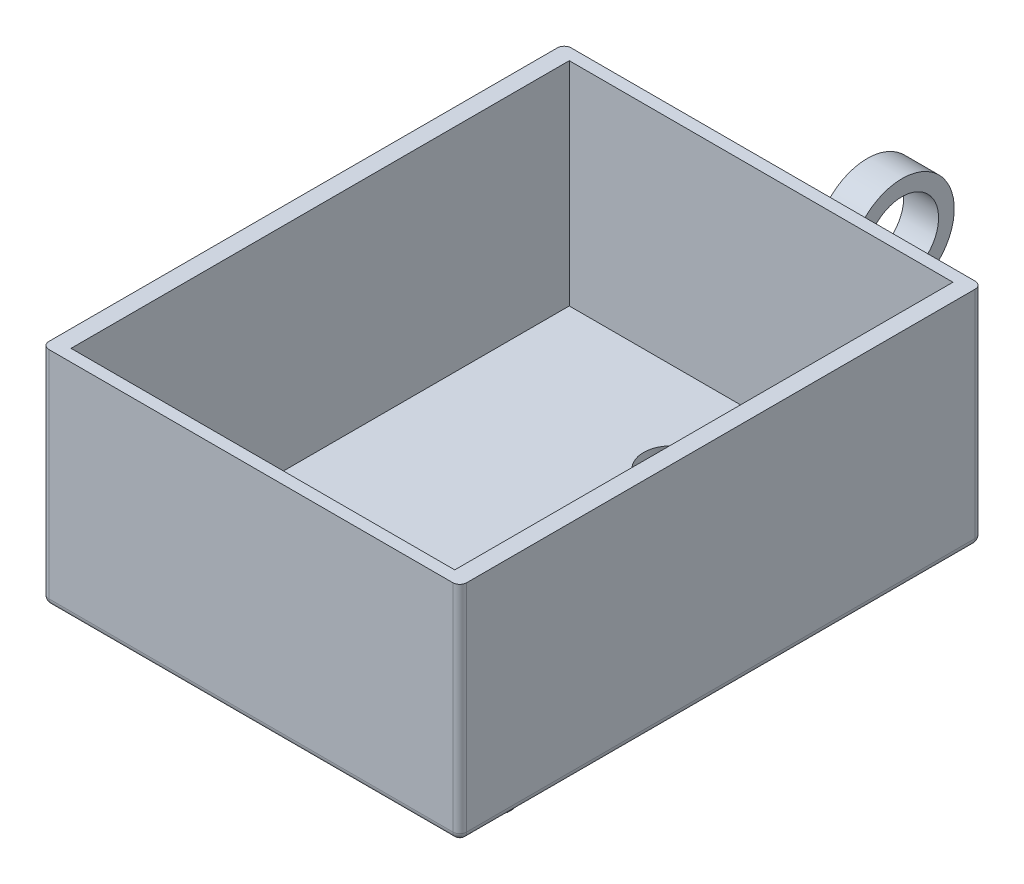
SolidWorks part; units mm, degrees
ref_plane "Front Plane" through (0, 0, 0) normal (0, 0, 1) x (1, 0, 0)
ref_plane "Top Plane" through (0, 0, 0) normal (0, 1, 0) x (1, 0, 0)
ref_plane "Right Plane" through (0, 0, 0) normal (1, 0, 0) x (0, 0, -1)
sketch "Sketch1" plane through (0, 0, 0) normal (0, 0, 1) x (1, 0, 0)
  line L1 (0, 0) -> (60, 0)
  line L2 (0, 0) -> (0, 32)
  line L3 (0, 32) -> (60, 32)
  line L4 (60, 0) -> (60, 32)
  dimension "D1" = 32
  dimension "D2" = 60
extrude "Boss-Extrude1" add sketch "Sketch1" along normal blind 75
sketch "Sketch2" plane through (0, 32, 0) normal (0, 1, 0) x (1, 0, 0)
  line L0 (0, 0) -> (2.452, -1.7285)
  line L1 (57.548, -1.7285) -> (60, 0)
  line L2 (2.452, -1.7285) -> (57.548, -1.7285)
  line L3 (2.452, -1.7285) -> (2.452, -73.2715)
  line L4 (2.452, -73.2715) -> (57.548, -73.2715)
  line L5 (57.548, -1.7285) -> (57.548, -73.2715)
  line L6 (0, -75) -> (2.452, -73.2715)
  line L7 (60, -75) -> (57.548, -73.2715)
  dimension "D1" = 3
extrude "Cut-Extrude1" cut sketch "Sketch2" along direction (0, -1, 0) on the side against the normal offset from surface (30.5 mm away) 1.5 contours L5 L2 L3 L4
sketch "Sketch3" plane through (0, 0, 0) normal (0, 0, -1) x (-1, 0, 0)
  line L0 (-30, 32) -> (-30, 0)
  line L1 (-60, 32) -> (0, 32) construction
  line L2 (0, 0) -> (-60, 0) construction
  line L4 (-32.5, 13.5) -> (-27.5, 13.5)
  line L5 (-32.5, 13.5) -> (-32.5, 18.5)
  line L6 (-32.5, 18.5) -> (-27.5, 18.5)
  line L7 (-27.5, 13.5) -> (-27.5, 18.5)
  line L8 (-32.5, 13.5) -> (-27.5, 18.5) construction
  line L9 (-32.5, 18.5) -> (-27.5, 13.5) construction
  point P6 (-30, 16)
  dimension "D1" = 5
  dimension "D2" = 5
extrude "Boss-Extrude2" add sketch "Sketch3" along normal blind 10 contours L4 L7 L6 L0 | L6 L5 L4 L0
sketch "Sketch4" plane through (27.5, 0, 0) normal (-1, 0, 0) x (0, 0, 1)
  line L0 (-10, 16) -> (-16, 16)
  line L1 (-10, 13.5) -> (-10, 18.5) construction
  circle A0 centre (-16, 16) radius 5.25
  circle A1 centre (-16, 16) radius 7.5
  dimension "D1" = 10.5
  dimension "D2" = 15
  dimension "D3" = 6
extrude "Boss-Extrude3" add sketch "Sketch4" against normal up to surface (5 mm away) separate body
sketch "Sketch8" plane through (0, 0, 73.2715) normal (0, 0, -1) x (-1, 0, 0)
  line L0 (-30, 1.5) -> (-30, 6.873)
  line L1 (-57.548, 1.5) -> (-2.452, 1.5) construction
  line L3 (-55, 6.5) -> (-5, 6.5)
  line L4 (-55, 6.5) -> (-55, 26.5)
  line L5 (-55, 26.5) -> (-5, 26.5)
  line L6 (-5, 6.5) -> (-5, 26.5)
  line L7 (-55, 6.5) -> (-5, 26.5) construction
  line L8 (-55, 26.5) -> (-5, 6.5) construction
  point P4 (-30, 16.5)
  dimension "D1" = 5
  dimension "D2" = 50
  dimension "D3" = 20
extrude "Boss-Extrude5" add sketch "Sketch8" along normal blind 0.1 contours L3 L6 L5 L4
sketch "Sketch9" plane through (0, 1.5, 0) normal (0, 1, 0) x (1, 0, 0)
  line L0 (30, -53.2715) -> (30, -73.2715)
  line L3 (30, -53.2715) -> (30, -27.5)
  line L4 (57.548, -73.2715) -> (2.452, -73.2715) construction
  line L5 (30, -27.5) -> (30, -1.7285)
  line L6 (57.548, -1.7285) -> (2.452, -1.7285) construction
  circle A2 centre (30, -40.3857) radius 2.75
  circle A3 centre (30, -14.6143) radius 4
  dimension "D1" = 20
  dimension "D2" = 8
  dimension "D3" = 5.5
extrude "Cut-Extrude2" cut sketch "Sketch9" against normal blind 20 contours L3 A2 | L3 A2 | L5 A3 | L5 A3
sketch "Sketch10" plane through (2.452, 0, 0) normal (1, 0, 0) x (0, 0, -1)
  line L0 (-73.2715, 16.5) -> (-68.7715, 16.5)
  line L2 (-71.2715, 12.5) -> (-66.2715, 12.5)
  line L3 (-71.2715, 12.5) -> (-71.2715, 20.5)
  line L4 (-73.2715, 26.5) -> (-73.2715, 6.5)
  line L5 (-73.1715, 26.5) -> (-73.2715, 26.5)
  line L6 (-73.1715, 6.5) -> (-73.1715, 26.5)
  line L7 (-73.2715, 6.5) -> (-73.1715, 6.5)
  line L8 (-73.2715, 26.5) -> (-73.2715, 6.5)
  line L9 (-73.1715, 26.5) -> (-73.2715, 26.5)
  line L10 (-73.1715, 6.5) -> (-73.1715, 26.5)
  line L11 (-73.2715, 6.5) -> (-73.1715, 6.5)
  line L12 (-71.2715, 20.5) -> (-66.2715, 20.5)
  line L13 (-66.2715, 12.5) -> (-66.2715, 20.5)
  line L14 (-71.2715, 12.5) -> (-66.2715, 20.5) construction
  line L15 (-71.2715, 20.5) -> (-66.2715, 12.5) construction
  dimension "D2" = 8
  dimension "D3" = 5
  dimension "D4" = 4.5
  dimension "D1" = 0
extrude "Cut-Extrude3" cut sketch "Sketch10" against normal blind 20
fillet "Fillet2" radius 2 4 edges at (27.5, 18.5, -5) (32.5, 18.5, -5) (32.5, 13.5, -5) (27.5, 13.5, -5)
fillet "Fillet4" radius 1 8 edges at (60, 16, 0) (60, 16, 75) (0, 16, 75) (0, 16, 0) (30, 0, 0) (60, 0, 37.5) (0, 0, 37.5) (30, 0, 75)
sketch "Sketch11" plane through (0, 0, 0) normal (0, 0, -1) x (-1, 0, 0)
  line L0 (-32.5, 16) -> (-49.2896, 16)
  line L1 (-32.5, 15.5) -> (-32.5, 16.5) construction
  line L3 (-46.2896, 13) -> (-52.2896, 13)
  line L4 (-46.2896, 13) -> (-46.2896, 19)
  line L5 (-46.2896, 19) -> (-52.2896, 19)
  line L6 (-52.2896, 13) -> (-52.2896, 19)
  line L7 (-46.2896, 13) -> (-52.2896, 19) construction
  line L8 (-46.2896, 19) -> (-52.2896, 13) construction
  dimension "D1" = 6
  dimension "D2" = 6
extrude "Cut-Extrude4" cut sketch "Sketch11" against normal blind 10
sketch "Sketch12" plane through (0, 0, 0) normal (0, -1, 0) x (-1, 0, 0)
  text T0 "L" font "Century Gothic" height 10
  text T1 "E" font "Century Gothic" height 10
  text T2 "D" font "Century Gothic" height 10
  point P0 (0, 0)
  dimension "D6" = 74
extrude "Boss-Extrude6" add sketch "Sketch12" along normal blind 2
